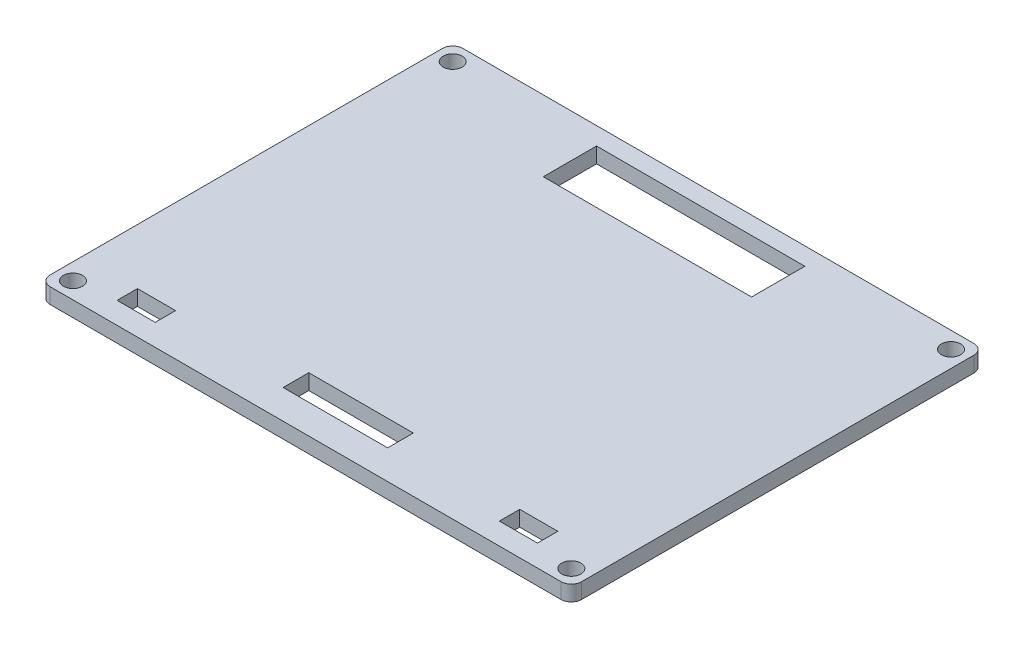
SolidWorks part; units mm, degrees
ref_plane "前视基准面" through (0, 0, 0) normal (0, 0, 1) x (1, 0, 0)
ref_plane "上视基准面" through (0, 0, 0) normal (0, 1, 0) x (1, 0, 0)
ref_plane "右视基准面" through (0, 0, 0) normal (1, 0, 0) x (0, 0, -1)
sketch "草图1" plane through (0, 0, 0) normal (0, 1, 0) x (1, 0, 0)
  line L0 (-51.5, 40) -> (-48.2968, 36.7968) construction
  line L1 (49.5, -40) -> (-49.5, -40)
  line L2 (51.5, -38) -> (51.5, 38)
  line L3 (49.5, 40) -> (-49.5, 40)
  line L4 (-51.5, -38) -> (-51.5, 38)
  line L5 (51.5, -40) -> (-51.5, 40) construction
  line L6 (51.5, 40) -> (-51.5, -40) construction
  line L7 (20.1874, 26.2491) -> (-20.1874, 26.2491)
  line L8 (20.1874, 26.2491) -> (20.1874, 36.5704)
  line L9 (20.1874, 36.5704) -> (-20.1874, 36.5704)
  line L10 (-20.1874, 26.2491) -> (-20.1874, 36.5704)
  line L11 (20.1874, 26.2491) -> (-20.1874, 36.5704) construction
  line L12 (20.1874, 36.5704) -> (-20.1874, 26.2491) construction
  line L13 (0, 31.4098) -> (0, -40) construction
  line L14 (51.5, 0) -> (-51.5, 0)
  line L15 (33.3536, -35.8039) -> (40.7411, -35.8039)
  line L16 (-10.0207, -29.3673) -> (10.2401, -29.3673)
  line L17 (-10.0207, -29.3673) -> (-10.0207, -34.3411)
  line L18 (-10.0207, -34.3411) -> (10.2401, -34.3411)
  line L19 (10.2401, -29.3673) -> (10.2401, -34.3411)
  line L20 (-33.3536, -31.8542) -> (-40.7411, -31.8542)
  line L21 (-33.3536, -31.8542) -> (-33.3536, -35.8039)
  line L22 (-33.3536, -35.8039) -> (-40.7411, -35.8039)
  line L23 (-40.7411, -31.8542) -> (-40.7411, -35.8039)
  line L24 (40.7411, -31.8542) -> (40.7411, -35.8039)
  line L25 (33.3536, -31.8542) -> (40.7411, -31.8542)
  line L26 (33.3536, -31.8542) -> (33.3536, -35.8039)
  circle A0 centre (-48.2968, 36.7968) radius 1.85
  circle A1 centre (48.2968, 36.7968) radius 1.85
  circle A2 centre (48.2968, -36.7968) radius 1.85
  circle A3 centre (-48.2968, -36.7968) radius 1.85
  arc A4 (-49.5, -40) -> (-51.5, -38) centre (-49.5, -38) cw
  arc A5 (49.5, -40) -> (51.5, -38) centre (49.5, -38) ccw
  arc A6 (51.5, 38) -> (49.5, 40) centre (49.5, 38) ccw
  arc A7 (-49.5, 40) -> (-51.5, 38) centre (-49.5, 38) ccw
  point P0 (0, 0)
  point P6 (0, 31.4098)
  point P18 (0, 0)
  dimension "D4" = 2
  dimension "D1" = 103
  dimension "D2" = 80
  dimension "D3" = 45
extrude "凸台-拉伸1" add sketch "草图1" along normal blind 3 contours L3 A7 L4 L14 L2 A6 L7 L10 L9 L8 A0 A1 | L1 A5 L2 L14 L4 A4 A3 A2
